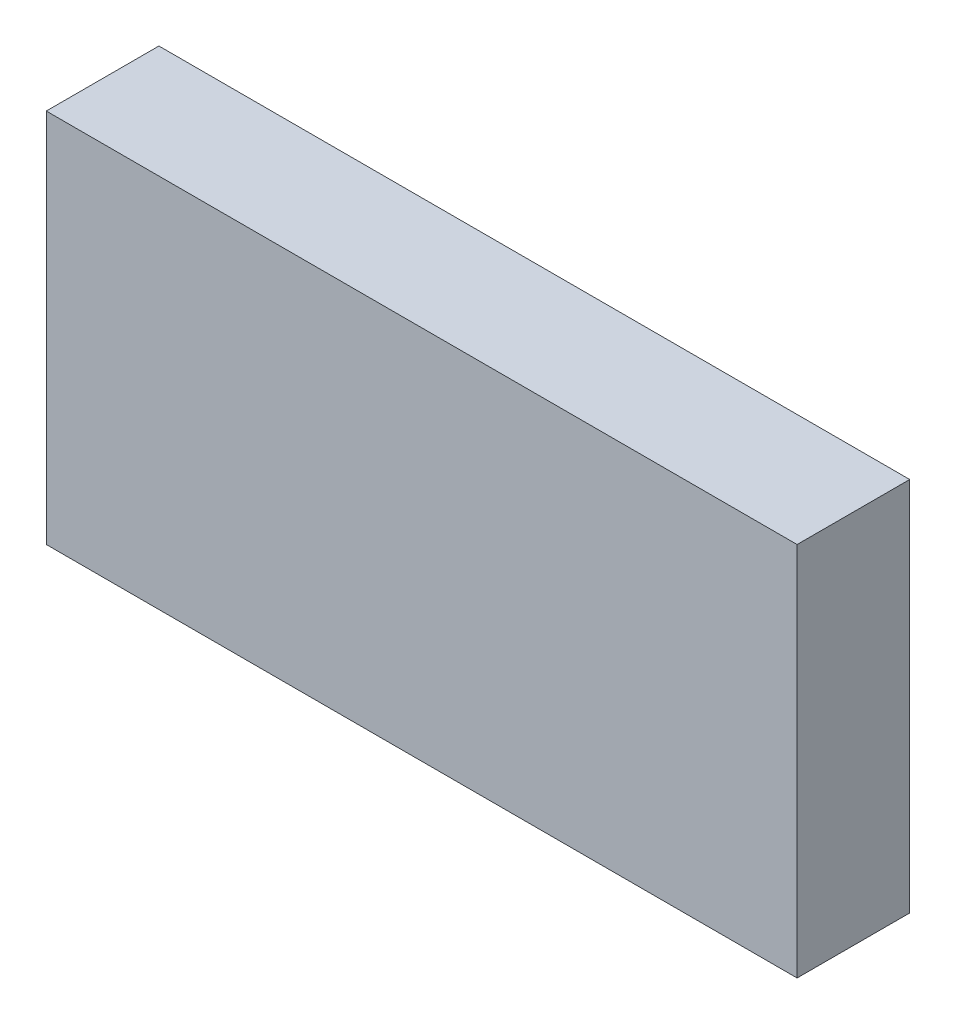
SolidWorks part; units mm, degrees
material "Polyethylene Cross-Linked"
ref_plane "Front Plane" through (0, 0, 0) normal (0, 0, 1) x (1, 0, 0)
ref_plane "Top Plane" through (0, 0, 0) normal (0, 1, 0) x (1, 0, 0)
ref_plane "Right Plane" through (0, 0, 0) normal (1, 0, 0) x (0, 0, -1)
sketch "Sketch1" plane through (0, 0, 0) normal (0, 0, 1) x (1, 0, 0)
  line L1 (0, 0) -> (1000, 0)
  line L2 (0, 0) -> (0, 500)
  line L3 (0, 500) -> (1000, 500)
  line L4 (1000, 0) -> (1000, 500)
  dimension "D1" = 1000
  dimension "D2" = 500
extrude "Boss-Extrude1" add sketch "Sketch1" along normal blind 150
